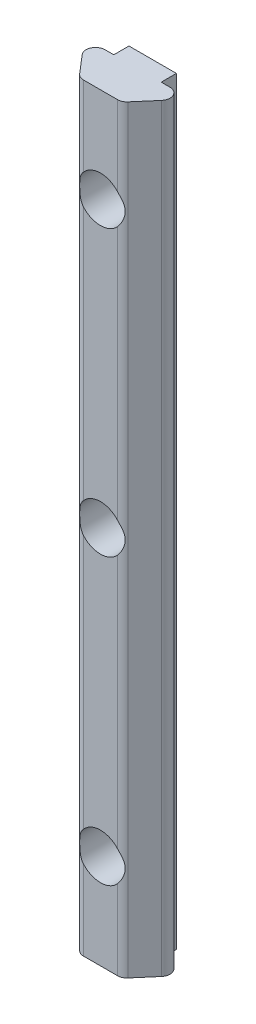
SolidWorks part; units mm, degrees
ref_plane "Front Plane" through (0, 0, 0) normal (0, 0, 1) x (1, 0, 0)
ref_plane "Top Plane" through (0, 0, 0) normal (0, 1, 0) x (1, 0, 0)
ref_plane "Right Plane" through (0, 0, 0) normal (1, 0, 0) x (0, 0, -1)
sketch "Sketch1" plane through (0, 0, 0) normal (0, 1, 0) x (1, 0, 0)
  line L0 (0.5833, 0) -> (5.1317, 0)
  line L1 (-1.4894, 4.953) -> (-0.3175, 4.953)
  line L2 (6.0951, 0.4425) -> (8.1678, 2.8555)
  line L3 (-2.4528, 2.8555) -> (-0.3801, 0.4425)
  line L4 (6.0325, 4.953) -> (7.2044, 4.953)
  line L6 (-0.3175, 4.953) -> (-0.3175, 6.985)
  line L7 (-0.3175, 6.985) -> (6.0325, 6.985)
  line L8 (6.0325, 4.953) -> (6.0325, 6.985)
  arc A0 (7.2044, 4.953) -> (8.1678, 2.8555) centre (7.2044, 3.683) cw
  arc A1 (-1.4894, 4.953) -> (-2.4528, 2.8555) centre (-1.4894, 3.683) ccw
  arc A2 (5.1317, 0) -> (6.0951, 0.4425) centre (5.1317, 1.27) ccw
  arc A3 (0.5833, 0) -> (-0.3801, 0.4425) centre (0.5833, 1.27) cw
  point P5 (2.8575, 0)
  point P8 (9.9695, 4.953)
  point P11 (-4.2545, 4.953)
  point P14 (5.715, 0)
  point P17 (0, 0)
  dimension "D5" = 1.27
  dimension "D6" = 1.27
  dimension "D1" = 5.715
  dimension "D2" = 14.224
  dimension "D3" = 4.2545
  dimension "D4" = 4.953
  dimension "D7" = 6.35
  dimension "D8" = 0.3175
  dimension "D9" = 2.032
extrude "Boss-Extrude1" add sketch "Sketch1" along normal blind 101.6 contours L6 L7 L8 L4 A0 L2 A2 L0 A3 L3 A1 L1
sketch "Sketch2" plane through (0, 0, -6.985) normal (0, 0, -1) x (-1, 0, 0)
  line L0 (-2.8575, 101.6) -> (-2.8575, 0) construction
  line L1 (0.3175, 101.6) -> (-6.0325, 101.6) construction
  line L2 (0.3175, 0) -> (-6.0325, 0) construction
  circle A0 centre (-2.8575, 50.8) radius 3.048
  circle A3 centre (-2.8575, 88.9) radius 3.048
  circle A4 centre (-2.8575, 12.7) radius 3.048
  dimension "D1" = 6.096
  dimension "D2" = 2
  dimension "D3" = 2
extrude "Cut-Extrude4" cut sketch "Sketch2" against normal blind 127
